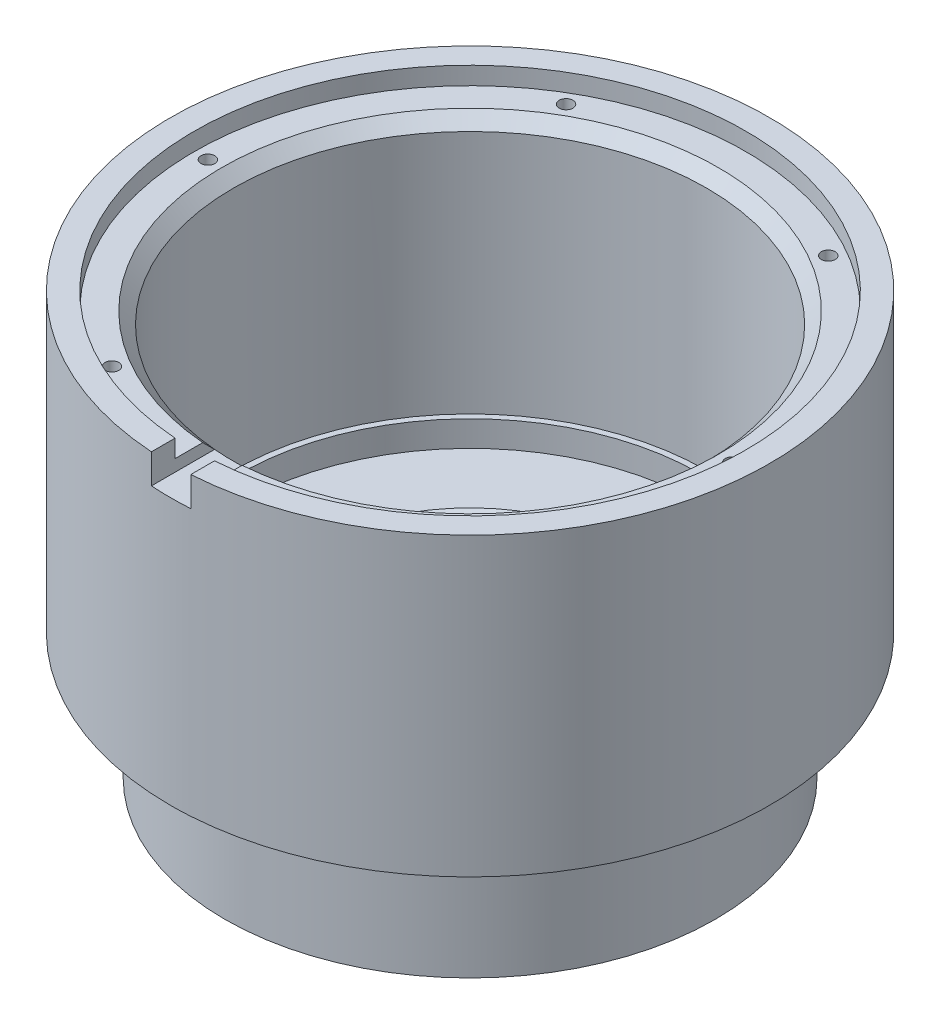
SolidWorks part; units mm, degrees
material "1060 Alloy"
ref_plane "Front Plane" through (0, 0, 0) normal (0, 0, 1) x (1, 0, 0)
ref_plane "Top Plane" through (0, 0, 0) normal (0, 1, 0) x (1, 0, 0)
ref_plane "Right Plane" through (0, 0, 0) normal (1, 0, 0) x (0, 0, -1)
sketch "Sketch7" plane through (0, 0, 0) normal (0, 0, 1) x (1, 0, 0)
  line L0 (0, -30.2319) -> (0, 30.2319) construction
  line L1 (-38.0375, 39.31) -> (-35.0375, 39.31)
  line L2 (-35.0375, 39.31) -> (-35.0375, 37.06)
  line L3 (-35.0375, 37.06) -> (-30.0375, 37.06)
  line L7 (-20.0375, 1.25) -> (-29.2875, 1.25)
  line L8 (-12.5, -1.25) -> (-12.5, -14.25)
  line L9 (-12.5, -14.25) -> (-38.0375, -14.25)
  line L10 (-38.0375, -14.25) -> (-38.0375, 39.31)
  line L11 (-16.2688, 0) -> (0, 0) construction
  line L12 (-20.0375, 1.25) -> (-12.5, -1.25)
  line L13 (-30.0375, 37.06) -> (-30.0375, 4.505)
  line L14 (-30.0375, 4.505) -> (-29.2875, 4.505)
  line L15 (-29.2875, 4.505) -> (-29.2875, 1.25)
  point P4 (0, 0)
  point P19 (-16.2688, 0)
  point P20 (-32.5375, 37.06)
  dimension "D1" = 3
  dimension "D2" = 2.25
  dimension "D3" = 5
  dimension "D6" = 13
  dimension "D9" = 12.5
  dimension "D5" = 35.81
  dimension "D7" = 2.5
  dimension "D4" = 30.0375
  dimension "D8" = 32.555
  dimension "D10" = 0.75
  dimension "D11" = 10
revolve "Base Motor Housing" add sketch "Sketch7" angle 360 about L0
chamfer "Chamfer1" distance 1.5 angle 45 1 edges at (0, 37.06, -30.0375)
ref_plane "Chamfer plane" through (0, 35.56, 0) normal (0, -1, 0) x (-1, 0, 0)
sketch "Sketch8" plane through (0, 39.31, 0) normal (0, 1, 0) x (1, 0, 0)
  line L0 (0, 0) -> (0, -38.0375) construction
  line L1 (-2.5, -38.0375) -> (2.5, -38.0375)
  line L2 (-2.5, -38.0375) -> (-2.5, -29.9333)
  line L3 (-2.5, -29.9333) -> (2.5, -29.9333)
  line L4 (2.5, -38.0375) -> (2.5, -29.9333)
  circle A0 centre (0, 0) radius 38.0375 construction
  circle A2 centre (0, 0) radius 30.0375 construction
  point P10 (0, -38.0375)
  dimension "D1" = 5
extrude "Wire Hole" cut sketch "Sketch8" against normal up to surface (3.75 mm away)
sketch "Sketch9" plane through (0, 37.06, 0) normal (0, 1, 0) x (1, 0, 0)
  line L0 (-31.5375, 0) -> (-35.0375, 0) construction
  circle A2 centre (0, 0) radius 33.2875 construction
  circle A3 centre (-33.2875, 0) radius 0.875
  circle A4 centre (-16.6437, 28.8278) radius 0.875
  circle A5 centre (16.6437, 28.8278) radius 0.875
  circle A6 centre (33.2875, 0) radius 0.875
  circle A7 centre (16.6438, -28.8278) radius 0.875
  circle A8 centre (-16.6437, -28.8278) radius 0.875
  arc A9 (2.5, -34.9482) -> (-2.5, -34.9482) centre (0, 0) ccw construction
  arc A10 (2.5, -34.9482) -> (-2.5, -34.9482) centre (0, 0) ccw construction
  arc A11 (2.5, -31.4383) -> (-2.5, -31.4383) centre (0, 0) ccw construction
  arc A14 (2.2186, -31.4594) -> (-2.2186, -31.4594) centre (0, 0) ccw construction
  point P21 (0, 0)
  point P31 (-33.2875, 0)
  dimension "D2" = 1.75
  dimension "D3" = 6
extrude "Front-Holes" cut sketch "Sketch9" against normal blind 6
sketch "Sketch10" plane through (0, -14.25, 0) normal (0, -1, 0) x (1, 0, 0)
  line L0 (-12.5, 0) -> (-38.0375, 0) construction
  circle A2 centre (0, 0) radius 38.0375 construction
  circle A3 centre (0, 0) radius 38.0375 construction
  circle A4 centre (-25.2688, 0) radius 2.875
  circle A5 centre (-12.6344, 21.8834) radius 2.875
  circle A6 centre (12.6344, 21.8834) radius 2.875
  circle A7 centre (25.2688, 0) radius 2.875
  circle A8 centre (12.6344, -21.8834) radius 2.875
  circle A9 centre (-12.6344, -21.8834) radius 2.875
  circle A10 centre (0, 0) radius 25.2688 construction
  circle A11 centre (0, 0) radius 12.5 construction
  circle A12 centre (0, 0) radius 12.5 construction
  point P22 (0, 0)
  dimension "D1" = 5.75
  dimension "D2" = 6
extrude "Back-Holes" cut sketch "Sketch10" against normal blind 8
sketch "Sketch11" plane through (0, 0, 0) normal (0, 0, 1) x (1, 0, 0)
  line L0 (31.1438, -14.25) -> (31.1438, -2.25)
  line L1 (-38.0375, -14.25) -> (38.0375, -14.25) construction
  line L2 (31.1438, -2.25) -> (38.0375, 1.7301)
  line L3 (38.0375, -14.25) -> (38.0375, 39.31) construction
  line L4 (38.0375, 1.7301) -> (38.0375, -14.25)
  line L5 (38.0375, -14.25) -> (31.1438, -14.25)
  line L6 (12.5, -14.25) -> (28.1438, -14.25) construction
  line L7 (28.1438, -14.25) -> (28.1438, 39.31) construction
  line L8 (35.0375, 39.31) -> (-35.0375, 39.31) construction
  line L9 (31.1438, -2.25) -> (38.0375, -2.25) construction
  line L10 (0, 0) -> (0, -13.4206) construction
  dimension "D1" = 3
  dimension "D2" = 30
  dimension "D3" = 12
revolve "Cut-Revolve1" cut sketch "Sketch11" angle 360 about L10
equation "\"D2@Sketch9\"=\"Back_mount_hole\""
equation "\"Stator_OD\"= 60'No Tolerance given"
equation "\"A\"=35.81 'taken off spec sheet for 06808 (A)"
equation "\"Rotor_ID\"= 30'No Tolerance Given"
equation "\"back_bearing_Thickness\"= 8'randomish, thinnest off mcmaster"
equation "\"D6@Sketch7\"=\"back_bearing_Thickness\"+5"
equation "\"back_bearing_OD\"= 25'currently non-sense"
equation "\"D9@Sketch7\"=\"back_bearing_OD\"*1/2"
equation "\"D5@Sketch7\"=\"A\""
equation "\"Stator_Gap\"= 0.0375'+- 0.0125 (From 1.3.3.1 Kollmorgen manual)"
equation "\"Back_mount_hole\"= 1.75'To be tapped to M2 (USE LOCKTITE)"
equation "\"D1@Back-Holes\" = \"back_bearing_Thickness\""
equation "\"facePlate_Mount_Hole\"= 5.75'To be tapped to M6"
equation "\"D1@Sketch10\"=\"facePlate_Mount_Hole\""
equation "\"final_shaftD\"= 8'NEMA 23 shaft diameter. Should fit with harmonic?"
equation "\"back_bearing_ID\"= 15'Random number"
equation "\"final_shaftL\"= 50'random length. Idk"
equation "\"back_bearing_IDOD\"= 18'Random number, OD of the inner bearing ring"
equation "\"rotor_shaftD\"= \"Rotor_ID\" - (\"rotor-shaft_gap\")*2'"
equation "\"front_bearing_ID\"= 12'random"
equation "\"front_bearing_OD\"= 20'random"
equation "\"front_bearing_IDOD\"= 14'random"
equation "\"front_bearing_Thickness\"= 5'randomish, thinnest off mcmaster"
equation "\"rotor_thickness\"= 2.4'measured off CAD"
equation "\"rotor_height\"= 32.86'+-0.075 taken off spec sheet for 06826 (C)"
equation "\"D4@Sketch7\"=\"Stator_OD\"/2+\"Stator_Gap\""
equation "\"B\"= 26.3'+-0.35 taken off spec sheet for 06826"
equation "\"D8@Sketch7\"=(\"A\"-\"B\")/2+\"B\"+1.5"
equation "\"D11@Sketch7\"=\"Rotor_ID\"/2-5"
equation "\"D3@Sketch11\"=\"back_bearing_Thickness\"*1.5"
